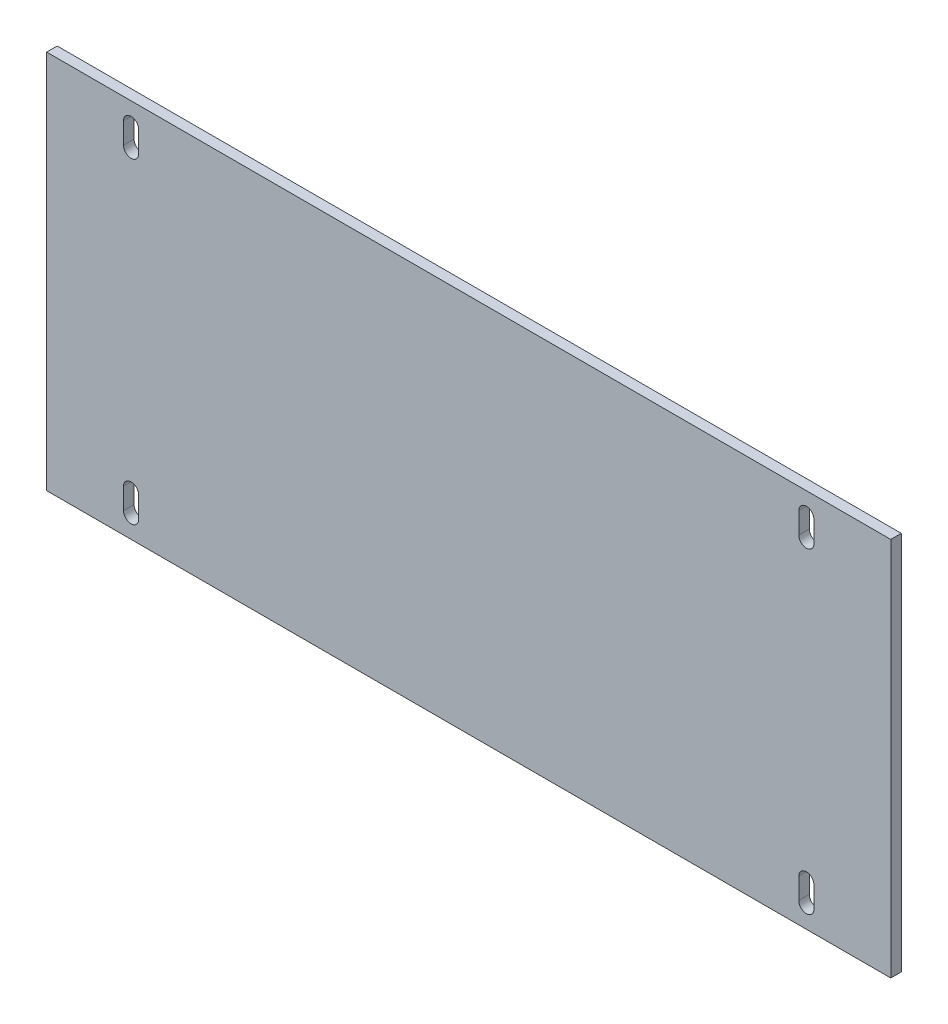
SolidWorks part; units mm, degrees
ref_plane "Front Plane" through (0, 0, 0) normal (0, 0, 1) x (1, 0, 0)
ref_plane "Top Plane" through (0, 0, 0) normal (0, 1, 0) x (1, 0, 0)
ref_plane "Right Plane" through (0, 0, 0) normal (1, 0, 0) x (0, 0, -1)
sketch "Sketch2" plane through (0, 0, 0) normal (0, 0, 1) x (1, 0, 0)
  line L1 (-200, -90) -> (200, -90)
  line L2 (-200, -90) -> (-200, 90)
  line L3 (-200, 90) -> (200, 90)
  line L4 (200, -90) -> (200, 90)
  line L5 (-200, -90) -> (200, 90) construction
  line L6 (-200, 90) -> (200, -90) construction
  point P0 (0, 0)
  dimension "D1" = 400
  dimension "D2" = 180
extrude "Boss-Extrude1" add sketch "Sketch2" along normal blind 5
sketch "Sketch3" plane through (0, 0, 5) normal (0, 0, 1) x (1, 0, 0)
  line L0 (-160, 80) -> (-160, 70) construction
  line L1 (-156.4, 80) -> (-156.4, 70)
  line L2 (-163.6, 80) -> (-163.6, 70)
  line L3 (-200, 90) -> (-200, -90) construction
  line L5 (200, 90) -> (-200, 90) construction
  arc A0 (-156.4, 80) -> (-163.6, 80) centre (-160, 80) ccw
  arc A1 (-163.6, 70) -> (-156.4, 70) centre (-160, 70) ccw
  point P2 (-160, 75)
  dimension "D4" = 3.6
  dimension "D1" = 40
  dimension "D2" = 20
  dimension "D3" = 10
extrude "Cut-Extrude1" cut sketch "Sketch3" against normal up to next
mirror "Mirror1" about plane through (0, 0, 0) normal (0, 1, 0) of "Cut-Extrude1" second plane through (0, 0, 0) second plane normal (1, 0, 0)
